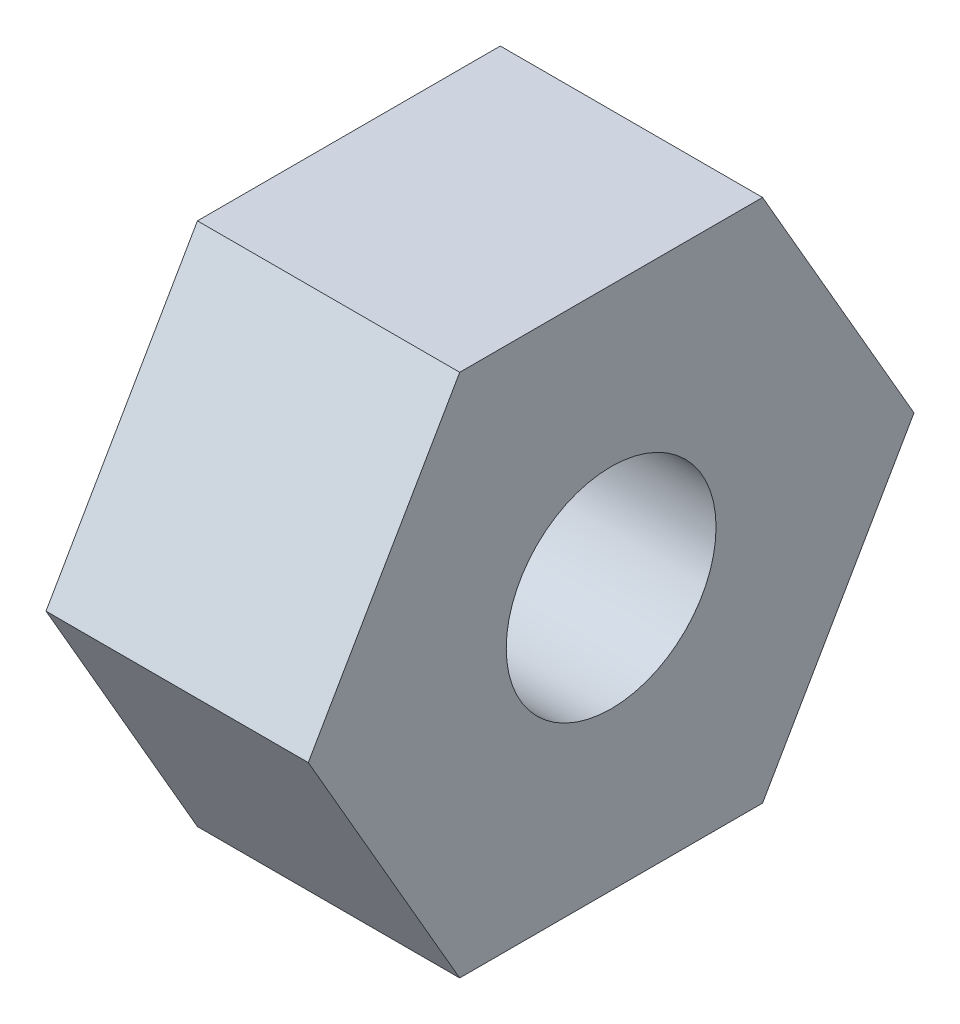
SolidWorks part; units mm, degrees
ref_plane "Front Plane" through (0, 0, 0) normal (0, 0, 1) x (1, 0, 0)
ref_plane "Top Plane" through (0, 0, 0) normal (0, 1, 0) x (1, 0, 0)
ref_plane "Right Plane" through (0, 0, 0) normal (1, 0, 0) x (0, 0, -1)
sketch "Sketch1" plane through (0, 0, 0) normal (1, 0, 0) x (0, 0, -1)
  line L1 (5.7735, 0) -> (2.8868, 5)
  line L2 (2.8868, 5) -> (-2.8868, 5)
  line L3 (-2.8868, 5) -> (-5.7735, 0)
  line L4 (-5.7735, 0) -> (-2.8868, -5)
  line L5 (-2.8868, -5) -> (2.8868, -5)
  line L6 (2.8868, -5) -> (5.7735, 0)
  circle A0 centre (0, 0) radius 5 construction
  dimension "D1" = 10
extrude "Boss-Extrude1" add sketch "Sketch1" along normal blind 5
sketch "Sketch4" plane through (0, 0, 0) normal (-1, 0, 0) x (0, 0, 1)
  circle A0 centre (0, 0) radius 2
  dimension "D1" = 4
extrude "Cut-Extrude1" cut sketch "Sketch4" against normal through all
